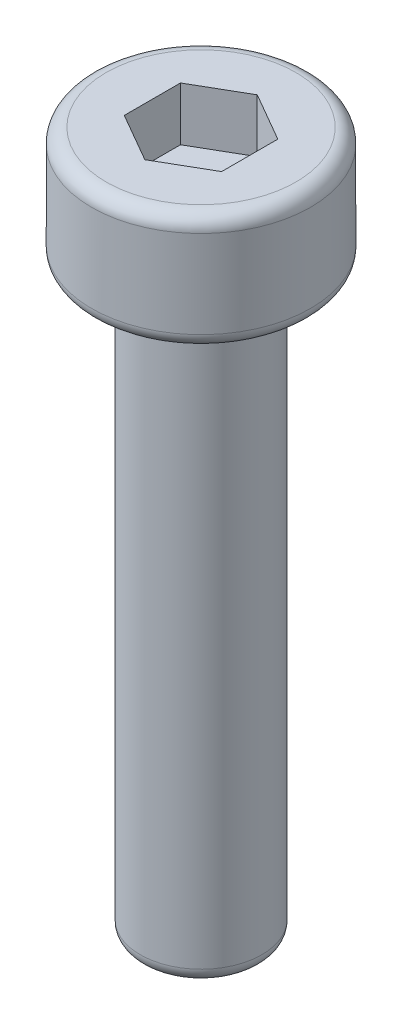
SolidWorks part; units mm, degrees
ref_plane "前视基准面" through (0, 0, 0) normal (0, 0, 1) x (1, 0, 0)
ref_plane "上视基准面" through (0, 0, 0) normal (0, 1, 0) x (1, 0, 0)
ref_plane "右视基准面" through (0, 0, 0) normal (1, 0, 0) x (0, 0, -1)
sketch "草图1" plane through (0, 0, 0) normal (0, 0, 1) x (1, 0, 0)
  line L0 (2.25, 0) -> (0, 0)
  line L1 (0, 0) -> (0, -2.4)
  line L2 (0, -2.4) -> (2.25, -2.4)
  line L3 (2.25, -2.4) -> (2.25, 0)
  line L4 (0, 0) -> (0, -2.4) construction
  dimension "D1" = 2.25
  dimension "D2" = 2.4
revolve "旋转1" add sketch "草图1" angle 360 about L4
sketch "草图2" plane through (0, -2.4, 0) normal (0, -1, 0) x (1, 0, 0)
  circle A0 centre (0, 0) radius 1.25
  dimension "D1" = 2.5
extrude "凸台-拉伸1" add sketch "草图2" along normal blind 12
sketch "草图3" plane through (0, 0, 0) normal (0, 1, 0) x (-1, 0, 0)
  line L1 (0, -1.1547) -> (1, -0.5774)
  line L2 (1, -0.5774) -> (1, 0.5774)
  line L3 (1, 0.5774) -> (0, 1.1547)
  line L4 (0, 1.1547) -> (-1, 0.5774)
  line L5 (-1, 0.5774) -> (-1, -0.5774)
  line L6 (-1, -0.5774) -> (0, -1.1547)
  circle A0 centre (0, 0) radius 1 construction
  dimension "D1" = 2
extrude "切除-拉伸1" cut sketch "草图3" against normal blind 1.1
fillet "圆角1" radius 0.3 3 edges at (0, -14.4, -1.25) (2.25, 0, 0) (2.25, -2.4, 0)
